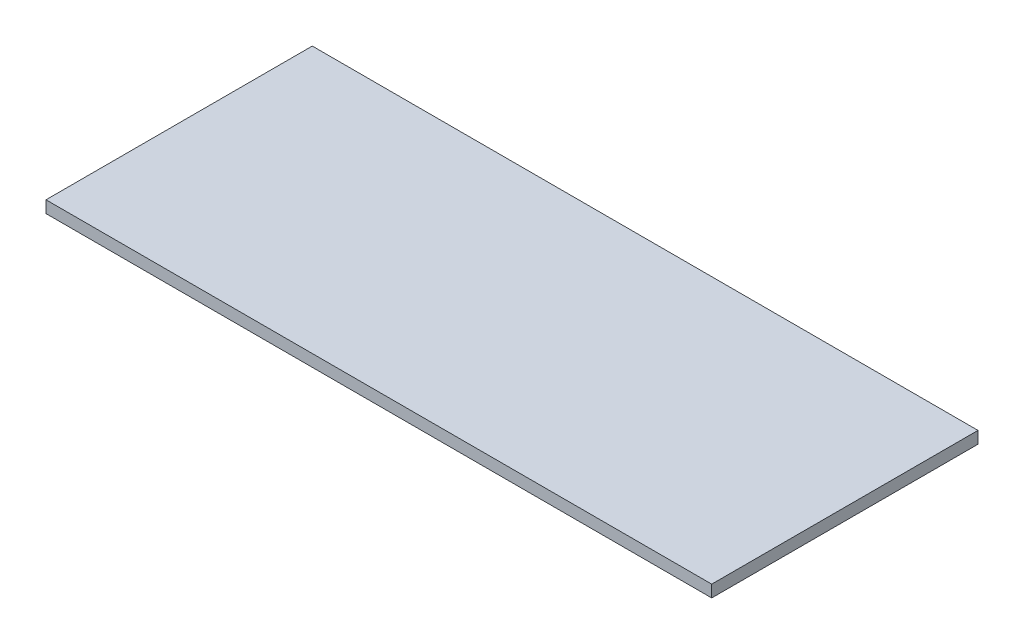
SolidWorks part; units mm, degrees
ref_plane "Front Plane" through (0, 0, 0) normal (0, 0, 1) x (1, 0, 0)
ref_plane "Top Plane" through (0, 0, 0) normal (0, 1, 0) x (1, 0, 0)
ref_plane "Right Plane" through (0, 0, 0) normal (1, 0, 0) x (0, 0, -1)
sketch "Esquisse1" plane through (0, 0, 0) normal (0, 1, 0) x (1, 0, 0)
  line L1 (-500, 200) -> (500, 200)
  line L2 (-500, 200) -> (-500, -200)
  line L3 (-500, -200) -> (500, -200)
  line L4 (500, 200) -> (500, -200)
  line L5 (-500, 200) -> (500, -200) construction
  line L6 (-500, -200) -> (500, 200) construction
  point P0 (0, 0)
extrude "Boss.-Extru.1" add sketch "Esquisse1" along normal blind 18
